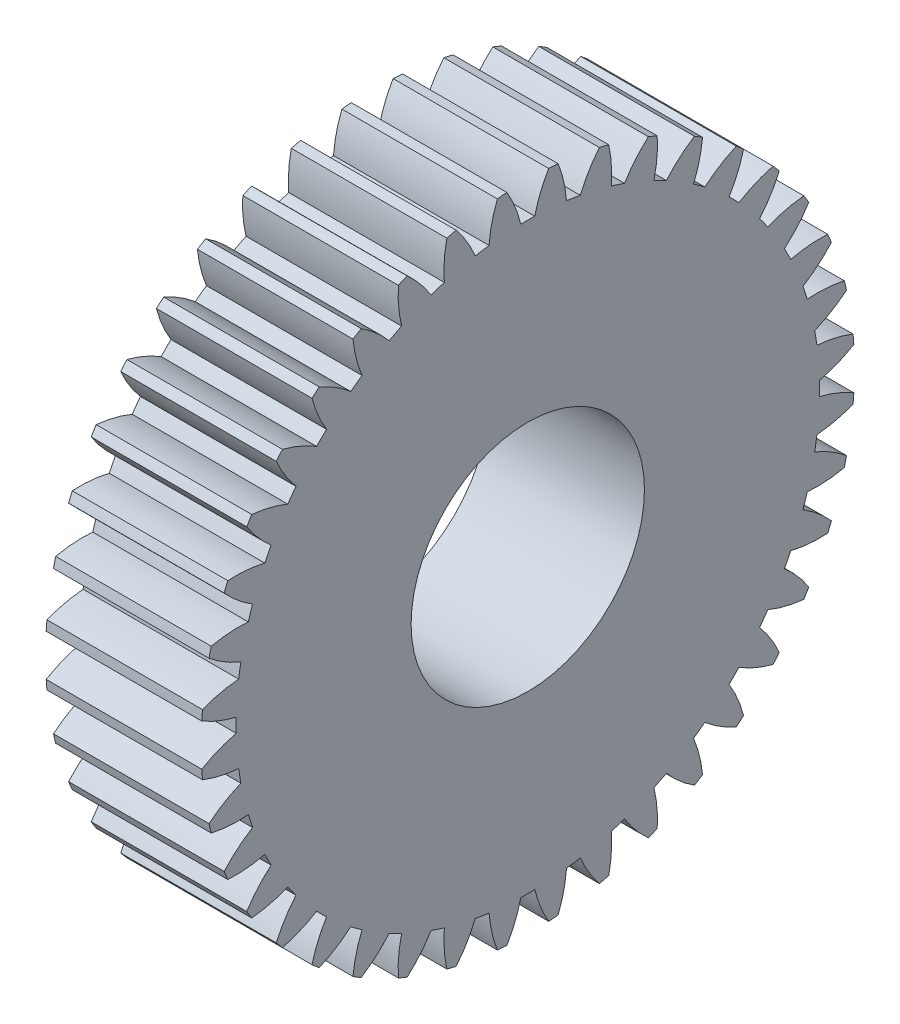
SolidWorks part; units mm, degrees
ref_plane "Plane1" through (0, 0, 0) normal (0, 0, 1) x (1, 0, 0)
ref_plane "Plane2" through (0, 0, 0) normal (0, 1, 0) x (1, 0, 0)
ref_plane "Plane3" through (0, 0, 0) normal (1, 0, 0) x (0, 0, -1)
sketch "HoldingSke" plane through (0, 0, 0) normal (0, 1, 0) x (1, 0, 0)
  line L0 (0, 0) -> (0.766, -0.6428)
  line L1 (-15, 0) -> (100, 0) construction
  line L2 (0, 0) -> (-2.1039, 2.3779)
  line L3 (0, 0) -> (-11.863, 4.5341)
  line L4 (0, 0) -> (6.6156, 5.5511)
  line L5 (0, 0) -> (-46.8476, -17.4728)
  line L6 (0, 0) -> (-8.2896, -5.593)
  line L7 (-2.1039, 2.3779) -> (8.6586, 51.2059)
  line L8 (-76.2, 54.61) -> (-73.9, 54.61)
  line L9 (-71.009, 38.7566) -> (-53.1078, 45.2721)
  line L10 (-76.2, 71.12) -> (104.1128, 71.12)
  line L11 (0, 0) -> (-10, 0)
  line L12 (-76.2, 101.6) -> (-76.162, 101.6)
  line L13 (24.9733, 27.94) -> (52.9518, 28.4284)
  line L14 (24.9733, 27.94) -> (24.9743, 27.94)
  line L15 (24.9733, 27.94) -> (100.4006, 29.5858)
  line L16 (-63.627, -1) -> (-12.827, -1)
  circle A0 centre (0, 0) radius 7.5
  circle A1 centre (0, 0) radius 18.749
  circle A2 centre (0, 0) radius 37.5
  circle A3 centre (0, 0) radius 7.5
  dimension "MHD" = 37.498
  dimension "Hub_dia" = 75
  dimension "Bore" = 15
  dimension "MBD" = 15
  dimension "Num_teeth" = 40
  dimension "Pitch" = 1
  dimension "Overall_len" = 50
  dimension "Show_teeth" = 40
  dimension "Thickness" = 10
  dimension "OAL" = 50.0001
  dimension "T_dim" = 2.3
  dimension "Ap" = 20
  dimension "H" = 19.05
  dimension "Pitch_radius" = 180.3128
  dimension "Width" = 10
  dimension "Backlash" = 0.038
  dimension "Addendum_fac" = 1
  dimension "Dedendum_fac" = 1.25
  dimension "Clearance_fac" = 0.25
  dimension "Dedendum_add" = 0.001
  dimension "Module" = 1
sketch "BasProSke" plane through (0, 0, 0) normal (0, 1, 0) x (1, 0, 0)
  line L0 (-10, 0) -> (60, 0) construction
  line L1 (0, 0) -> (0, 21)
  line L2 (0, 0) -> (10, 0)
  line L3 (10, 0) -> (10, 21)
  line L4 (10, 21) -> (0, 21)
  dimension "Thickness" = 10
  dimension "Diameter" = 42
revolve "Base-Revolve" add sketch "BasProSke" angle 360 about L0
sketch "TooCutSke" plane through (0, 0, 0) normal (1, 0, 0) x (0, 0, -1)
  line L1 (0, 0) -> (0, 107) construction
  line L2 (0, 0) -> (-0.8517, 19.9819) construction
  line L3 (0, 0) -> (-3.1363, 39.8509) construction
  line L4 (-0.8517, 19.9819) -> (-1.5682, 19.9255) construction
  arc A0 (0.4487, 18.7436) -> (-0.4487, 18.7436) centre (0, 0) ccw
  arc A1 (1.3547, 20.9817) -> (-1.3547, 20.9817) centre (0, 0) ccw
  circle A2 centre (0, 0) radius 20 construction
  circle A3 centre (0, 0) radius 18.7939 construction
  arc A4 (-0.4487, 18.7436) -> (-1.3547, 20.9817) centre (-8.2322, 16.895) ccw
  arc A5 (1.3547, 20.9817) -> (0.4487, 18.7436) centre (8.2322, 16.895) ccw
  dimension "Root_dia" = 37.498
  dimension "Overcut_dia" = 42.0508
  dimension "Pitch_dia" = 40
  dimension "Base_dia" = 37.5877
  dimension "Flank_rad" = 8
  dimension "Half_ang" = 4.5
  dimension "Half_CT" = 0.7187
extrude "ToothCut" cut sketch "TooCutSke" along normal through all
fillet "Breaks" [suppressed] radius 0.02
fillet "RootFillets" [suppressed] radius 0.251
pattern_circular "TeethCuts" count 40 every 9 about axis through (-10, 0, 0) along (1, 0, 0) of "ToothCut", "RootFillets", "Breaks"
sketch "HubNeaOneSke" plane through (0, 0, 0) normal (-1, 0, 0) x (0, 0, 1)
  circle A0 centre (0, 0) radius 18.749
  dimension "Diameter" = 37.498
extrude "HubNearOne" [suppressed] add sketch "HubNeaOneSke" along normal blind 40.0001
sketch "HubNeaBotSke" plane through (0, 0, 0) normal (-1, 0, 0) x (0, 0, 1)
  circle A0 centre (0, 0) radius 18.749
  dimension "Diameter" = 37.498
extrude "HubNearBoth" [suppressed] add sketch "HubNeaBotSke" along normal blind 20
ref_plane "FarPln" through (10, 0, 0) normal (1, 0, 0) x (0, 0, -1)
sketch "HubFarSke" plane through (10, 0, 0) normal (1, 0, 0) x (0, 0, -1)
  circle A0 centre (0, 0) radius 18.749
  dimension "Diameter" = 37.498
extrude "HubFar" [suppressed] add sketch "HubFarSke" along normal blind 20
sketch "BorSke" plane through (0, 0, 0) normal (1, 0, 0) x (0, 0, -1)
  circle A0 centre (0, 0) radius 7.5
  dimension "Diameter" = 15
extrude "Bore" cut sketch "BorSke" along normal mid plane 100.0001
sketch "KeySke" plane through (0, 0, 0) normal (1, 0, 0) x (0, 0, -1)
  line L0 (-2.5, 0) -> (-2.5, 9.8)
  line L1 (-2.5, 9.8) -> (2.5, 9.8)
  line L2 (2.5, 9.8) -> (2.5, 0)
  line L3 (0, 0) -> (0, 34) construction
  line L4 (-2.5, 0) -> (2.5, 0)
  dimension "Offset" = 9.8
  dimension "Width" = 5
extrude "Keyway" [suppressed] cut sketch "KeySke" along normal mid plane 100.0001
pattern_circular "Keyway2" [suppressed] count 2 every 90 about axis through (-10, 0, 0) along (1, 0, 0)
equation "' \"Module@HoldingSke\" = 6.35"
equation "' \"Num_teeth@HoldingSke\" = 12"
equation "' \"Ap@HoldingSke\" =  20"
equation "' \"Ap@HoldingSke\" = 20"
equation "' \"Width@HoldingSke\" = 0.5 * 25.4"
equation "' \"Hub_dia@HoldingSke\"= 1 * 25.4"
equation "' \"Hub_dia@HoldingSke\" = 1 * 25.4"
equation "' \"Overall_len@HoldingSke\" = 1.0 * 25.4"
equation "' \"Bore@HoldingSke\" = 0.75 * 25.4"
equation "' \"T_dim@HoldingSke\" = 0.1 * 25.4"
equation "' \"Width@KeySke\" = 0.25 * 25.4"
equation "' \"Show_teeth@HoldingSke\" = 13"
equation "' \"Backlash@HoldingSke\" = 0.009 * 25.4"
equation "' \"Addendum_fac@HoldingSke\" = 1.0"
equation "' \"Dedendum_fac@HoldingSke\" = 1.25"
equation "' \"Dedendum_add@HoldingSke\" = 0.00005 * 25.4"
equation "' \"Clearance_fac@HoldingSke\" = 0.25"
equation "\"Pitch@HoldingSke\" = 1 / \"Module@HoldingSke\""
equation "\"Overcut_dia@TooCutSke\" = (\"Num_teeth@HoldingSke\" + 2 * \"Addendum_fac@HoldingSke\") / \"Pitch@HoldingSke\" + 0.002 * 25.4"
equation "\"Pitch_dia@TooCutSke\" = \"Num_teeth@HoldingSke\" / \"Pitch@HoldingSke\""
equation "\"Base_dia@TooCutSke\" = \"Num_teeth@HoldingSke\" / \"Pitch@HoldingSke\" * cos((\"Ap@HoldingSke\"  * 3.14159265 / 180))"
equation "\"Root_dia@TooCutSke\" = (\"Num_teeth@HoldingSke\" + 2) / \"Pitch@HoldingSke\" - 2 * (\"Addendum_fac@HoldingSke\" + \"Dedendum_fac@HoldingSke\") / \"Pitch@HoldingSke\" - \"Dedendum_add@HoldingSke\" * 2"
equation "\"Half_ang@TooCutSke\" = 180 / \"Num_teeth@HoldingSke\""
equation "\"Half_CT@TooCutSke\" = \"Num_teeth@HoldingSke\" / \"Pitch@HoldingSke\" * sin((3.14159265 / 2 / \"Num_teeth@HoldingSke\")) / 2 - 7 * \"Backlash@HoldingSke\" / 4"
equation "\"Flank_rad@TooCutSke\" = \"Num_teeth@HoldingSke\" / \"Pitch@HoldingSke\" / 5"
equation "\"Radius@RootFillets\" = \"Clearance_fac@HoldingSke\" / \"Pitch@HoldingSke\" + \"Dedendum_add@HoldingSke\""
equation "\"Break_rad@Breaks\" = 0.02 / \"Pitch@HoldingSke\""
equation "\"Thickness@HoldingSke\" = \"Width@HoldingSke\""
equation "\"OAL@HoldingSke\" = \"Thickness@HoldingSke\""
equation "\"MHD@HoldingSke\" = (\"Num_teeth@HoldingSke\" + 2) / \"Pitch@HoldingSke\" - 2 * (\"Addendum_fac@HoldingSke\" + \"Dedendum_fac@HoldingSke\")  / \"Pitch@HoldingSke\" - \"Dedendum_add@HoldingSke\" * 2"
equation "\"MBD@HoldingSke\" = (\"Num_teeth@HoldingSke\" + 2) / \"Pitch@HoldingSke\" - 2 * (\"Addendum_fac@HoldingSke\" + \"Dedendum_fac@HoldingSke\")  / \"Pitch@HoldingSke\" - \"Dedendum_add@HoldingSke\" * 2 - 0.002 * 25.4"
equation "\"MHD@HoldingSke\" = ((sgn( \"MHD@HoldingSke\" - \"Hub_dia@HoldingSke\" )-1)*( \"MHD@HoldingSke\" - \"Hub_dia@HoldingSke\" ))/-2+ \"Hub_dia@HoldingSke\""
equation "\"MBD@HoldingSke\" = ((sgn( \"MBD@HoldingSke\" - \"Bore@HoldingSke\" )-1)*( \"MBD@HoldingSke\" - \"Bore@HoldingSke\" ))/-2+ \"Bore@HoldingSke\""
equation "\"OAL@HoldingSke\" = ((sgn( \"OAL@HoldingSke\" - \"Overall_len@HoldingSke\" )+1)*( \"OAL@HoldingSke\" - \"Overall_len@HoldingSke\" ))/2 + \"Overall_len@HoldingSke\" + 0.000002 * 25.4"
equation "\"Num_teeth@TeethCuts\" = int( \"Show_teeth@HoldingSke\" ) + 1"
equation "\"Num_teeth@TeethCuts\" = ((sgn( \"Num_teeth@TeethCuts\" - \"Num_teeth@HoldingSke\" )-1)*( \"Num_teeth@TeethCuts\" - \"Num_teeth@HoldingSke\" ))/-2+ \"Num_teeth@HoldingSke\""
equation "\"Num_teeth@TeethCuts\" = ((sgn( \"Num_teeth@TeethCuts\" - 2.0)+1)*( \"Num_teeth@TeethCuts\" - 2.0))/2 +2.0"
equation "\"Angle@TeethCuts\" = 360.0 / \"Num_teeth@HoldingSke\""
equation "\"Diameter@BasProSke\" = (\"Num_teeth@HoldingSke\" + 2 * \"Addendum_fac@HoldingSke\") / \"Pitch@HoldingSke\""
equation "\"Thickness@BasProSke\"  = \"Thickness@HoldingSke\""
equation "' \"Fillet_rad@BasProSke\" =  \"Thickness@HoldingSke\" * 0.05"
equation "' \"Fillet_rad@BasProSke\" = \"Thickness@HoldingSke\" * 0.05"
equation "\"MHD@HoldingSke\" = ((sgn( \"MHD@HoldingSke\" - \"Root_dia@TooCutSke\" )-1)*( \"MHD@HoldingSke\" - \"Root_dia@TooCutSke\" ))/-2+ \"Root_dia@TooCutSke\""
equation "\"Diameter@HubNeaOneSke\" = \"MHD@HoldingSke\""
equation "\"Length@HubNearOne\" = \"OAL@HoldingSke\" - \"Thickness@BasProSke\""
equation "\"Diameter@HubNeaBotSke\" = \"MHD@HoldingSke\""
equation "\"Length@HubNearBoth\" = ( \"OAL@HoldingSke\" - \"Thickness@BasProSke\" ) / 2.0"
equation "\"Thickness@FarPln\" = \"Thickness@BasProSke\""
equation "\"Diameter@HubFarSke\" = \"MHD@HoldingSke\""
equation "\"Length@HubFar\" = ( \"OAL@HoldingSke\" - \"Thickness@BasProSke\" ) / 2.0"
equation "\"Diameter@BorSke\" = \"MBD@HoldingSke\""
equation "\"D1@Bore\" = \"OAL@HoldingSke\" * 2.0"
equation "\"D1@Keyway\" = \"OAL@HoldingSke\" * 2.0"
equation "\"Offset@KeySke\" = \"T_dim@HoldingSke\" + \"MBD@HoldingSke\" / 2.0"
